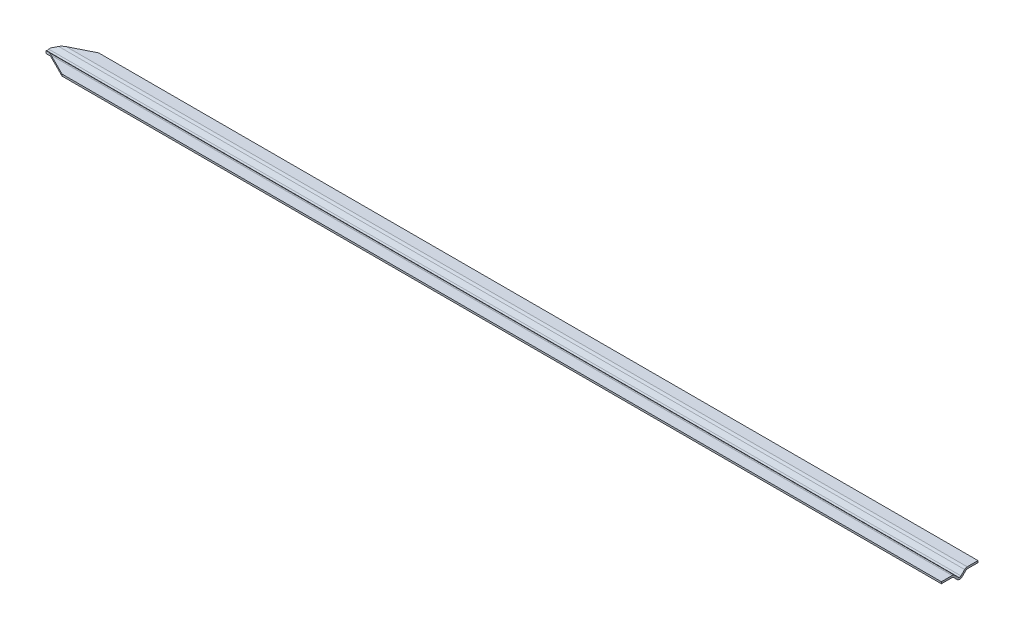
SolidWorks part; units mm, degrees
ref_plane "Спереди" through (0, 0, 0) normal (0, 0, 1) x (1, 0, 0)
ref_plane "Сверху" through (0, 0, 0) normal (0, 1, 0) x (1, 0, 0)
ref_plane "Справа" through (0, 0, 0) normal (1, 0, 0) x (0, 0, -1)
sketch "Эскиз1" plane through (0, 0, 0) normal (1, 0, 0) x (0, 0, -1)
  line L0 (-20, 0) -> (-7, 0)
  line L1 (-7, 0) -> (0, -7)
  line L2 (0, -7) -> (7, 0)
  line L3 (7, 0) -> (20, 0)
  line L4 (0, -3.8182) -> (0, 15.4545) construction
  dimension "D1" = 7
  dimension "D2" = 40
  dimension "D3" = 90
surface "Поверхность-Вытянуть1" sketch "Эскиз1" parameters "D1"=1000
thicken "Придать толщину1" surfaces to thicken 103 thickness 1 thickness side both sides parameters "D1"=1
fillet "Скругление1" radius 2 3 edges at (0, -5.5858, 0) (0, -1, 7.4142) (0, -1, -7.4142)
fillet "Скругление2" radius 4 3 edges at (0, -8.4142, 0) (0, 1, 6.5858) (0, 1, -6.5858)
sketch "Эскиз2" plane through (0, 0, 0) normal (0, 1, 0) x (1, 0, 0)
  line L0 (-500, 0) -> (604.5025, 0) construction
  line L1 (-500, 2.8284) -> (-500, 6.8284) construction
  line L2 (-460, -20) -> (-494.6334, -2.6833)
  line L3 (-494.6334, 2.6833) -> (-460, 20)
  line L4 (-500, -20) -> (500, -20) construction
  arc A0 (-494.6334, 2.6833) -> (-494.6334, -2.6833) centre (-493.2918, 0) ccw
  dimension "D2" = 3
  dimension "D1" = 40
extrude "Вырез-Вытянуть1" cut sketch "Эскиз2" against normal through all and the other way through all
equation "\"длина лезвия\"=1000"
equation "\"D1@Поверхность-Вытянуть1\"=\"длина лезвия\""
equation "\"радиус острия\"=3"
equation "\"D2@Эскиз2\"=\"радиус острия\""
equation "\"длина острия\"=40"
equation "\"D1@Эскиз2\"=\"длина острия\""
equation "\"ширина лезвия\"=40"
equation "\"D2@Эскиз1\"=\"ширина лезвия\""
equation "\"радиус сгиба\"=2"
equation "\"D1@Скругление1\"=\"радиус сгиба\""
equation "\"D1@Скругление2\"=\"радиус сгиба\" * 2"
equation "\"высота ребра жесткости\"=7"
equation "\"D1@Эскиз1\"=\"высота ребра жесткости\""
equation "\"толщина лезвия * 2\"=1"
equation "\"D1@Придать толщину1\"=\"толщина лезвия * 2\""
